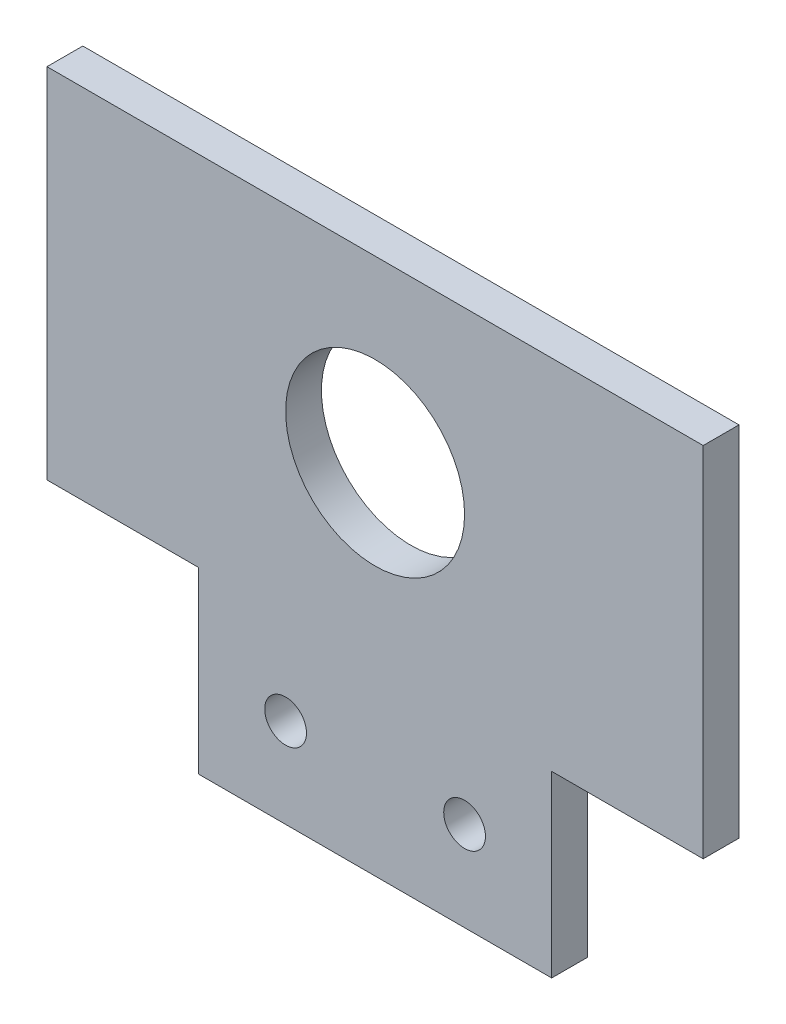
SolidWorks part; units mm, degrees
ref_plane "前视基准面" through (0, 0, 0) normal (0, 0, 1) x (1, 0, 0)
ref_plane "上视基准面" through (0, 0, 0) normal (0, 1, 0) x (1, 0, 0)
ref_plane "右视基准面" through (0, 0, 0) normal (1, 0, 0) x (0, 0, -1)
sketch "草图1" plane through (0, 0, 0) normal (0, 0, 1) x (1, 0, 0)
  line L0 (0, -1000) -> (0, 49000) construction
  line L1 (-14.8, -15) -> (14.8, -15)
  line L2 (-27.5, 0) -> (-27.5, 30)
  line L3 (-27.5, 30) -> (27.5, 30)
  line L4 (27.5, 0) -> (27.5, 30)
  line L5 (-14.8, -16.1455) -> (27.5, 30) construction
  line L6 (-27.5, 30) -> (14.8, -16.1455) construction
  line L7 (-1000, 0) -> (49000, 0) construction
  line L8 (-14.8, 0) -> (-27.5, 0)
  line L9 (14.8, 0) -> (27.5, 0)
  line L10 (-14.8, 0) -> (-14.8, -15)
  line L11 (14.8, 0) -> (14.8, -15)
  circle A0 centre (0, 15) radius 7.5
  point P0 (0, 0)
  dimension "D6" = 15
  dimension "D1" = 55
  dimension "D2" = 30
  dimension "D3" = 15
  dimension "D4" = 14.8
  dimension "D5" = 30
extrude "凸台-拉伸1" add sketch "草图1" along normal blind 3
sketch "草图2" plane through (0, 0, 3) normal (0, 0, 1) x (1, 0, 0)
  line L0 (0, -1000) -> (0, 49000) construction
  line L1 (-14.8, -15) -> (14.8, -15) construction
  circle A0 centre (-7.5, -7.5) radius 1.75
  circle A1 centre (7.5, -7.5) radius 1.75
  dimension "D1" = 7.5
  dimension "D3" = 3.5
  dimension "D2" = 7.5
extrude "切除-拉伸1" cut sketch "草图2" against normal blind 3
